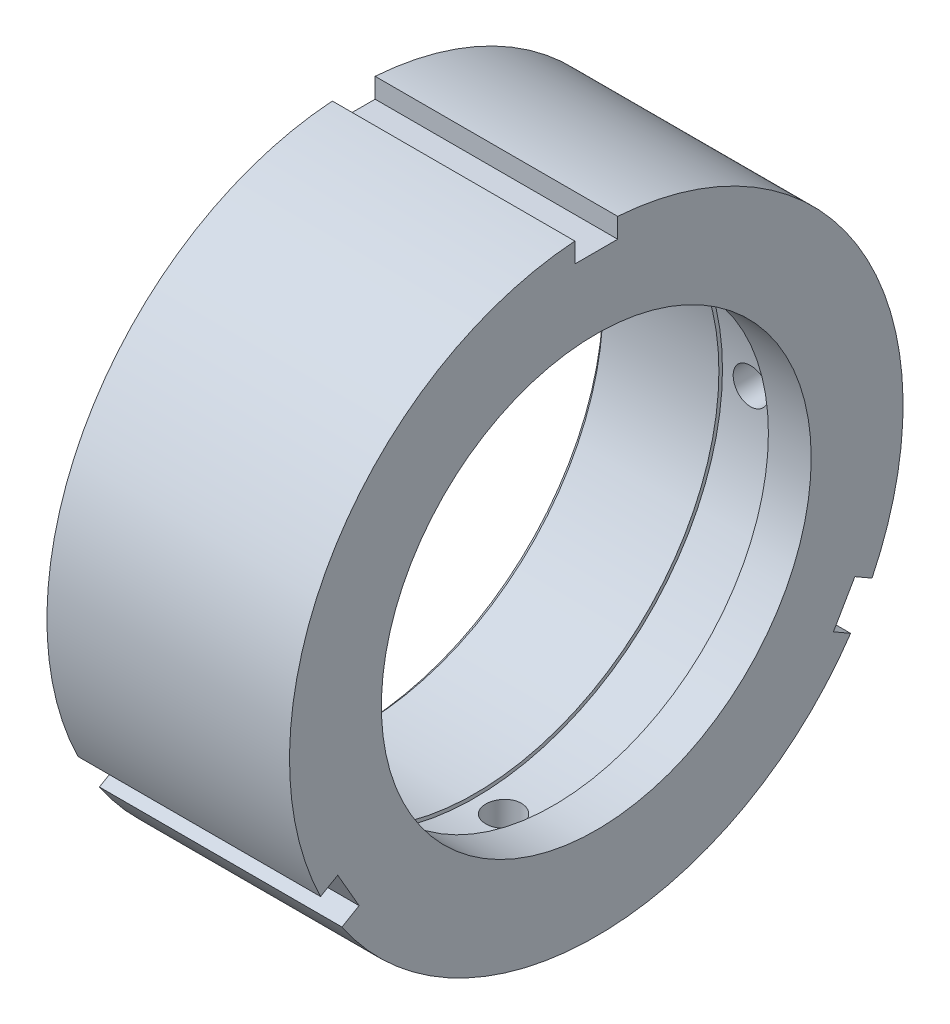
SolidWorks part; units mm, degrees
material "Low Carbon Steel"
ref_plane "Front Plane" through (0, 0, 0) normal (0, 0, 1) x (1, 0, 0)
ref_plane "Top Plane" through (0, 0, 0) normal (0, 1, 0) x (1, 0, 0)
ref_plane "Right Plane" through (0, 0, 0) normal (1, 0, 0) x (0, 0, -1)
sketch "Sketch1" plane through (0, 0, 0) normal (0, 0, 1) x (1, 0, 0)
  line L0 (0, 0) -> (-10.5172, 0) construction
  line L1 (0, 34.9501) -> (0, 43)
  line L2 (0, 43) -> (34, 43)
  line L3 (34, 43) -> (34, 30.125)
  line L4 (34, 30.125) -> (28, 30.125)
  line L5 (28, 30.125) -> (28, 34.6881)
  line L6 (17, 34.1881) -> (0.762, 34.1881)
  line L7 (17, 34.1881) -> (17, 34.6881)
  line L8 (17, 34.6881) -> (28, 34.6881)
  line L9 (0, 34.9501) -> (0.762, 34.1881)
  dimension "D1" = 6
  dimension "D2" = 34
  dimension "D3" = 86
  dimension "D4" = 60.25
  dimension "D5" = 0.5
  dimension "D6" = 11
  dimension "D7" = 68.3762
  dimension "D8" = 0.762
  dimension "D9" = 45
revolve "Revolve1" add sketch "Sketch1" angle 360 about L0
cosmetic thread "Cosmetic Thread1" parameters "D2"=72
sketch "Sketch2" plane through (0, 0, 0) normal (-1, 0, 0) x (0, 0, 1)
  line L1 (-3, 43.9896) -> (3, 43.9896)
  line L2 (-3, 43.9896) -> (-3, 40.116)
  line L3 (-3, 40.116) -> (3, 40.116)
  line L4 (3, 43.9896) -> (3, 40.116)
  circle A0 centre (0, 0) radius 30.125 construction
  point P4 (-3, 42.0528)
  dimension "D1" = 6
  dimension "D2" = 3
  dimension "D3" = 40.116
extrude "Cut-Extrude1" cut sketch "Sketch2" against normal through all
pattern_circular "CirPattern1" count 3 over 360 about axis through (0, 0, 0) along (1, 0, 0) of "Cut-Extrude1"
hole_wizard "M6 Tapped Hole1" positions "Sketch3" profile "Sketch4" tap size "M6" standard "Peddi DIN"
sketch "Sketch3" plane through (0, 0, 0) normal (0, 1, 0) x (1, 0, 0)
  line L0 (0, 3) -> (0, -3) construction
  point P0 (21, 0)
  dimension "D1" = 21
sketch "Sketch4" plane through (21, 0, 0) normal (1, 0, 0) x (0, 0, 1)
  line L0 (0, 0) -> (0, 43)
  line L1 (0, 43) -> (2.5, 43)
  line L2 (2.5, 43) -> (2.5, 0)
  line L5 (2.5, 0) -> (0, 0)
  line L11 (0, -6.35) -> (0, 107.95) construction
  dimension "Thru Tap Drill Dia." = 5
  dimension "Thru Tap Drill Depth" = 43
cosmetic thread "Hole Thread1" parameters "D2"=6
pattern_circular "CirPattern2" count 2 over 90 about axis through (0, 0, 0) along (1, 0, 0) of "M6 Tapped Hole1"
fillet "Fillet1" radius 0.762 1 edges at (28, 0, -34.6881)
